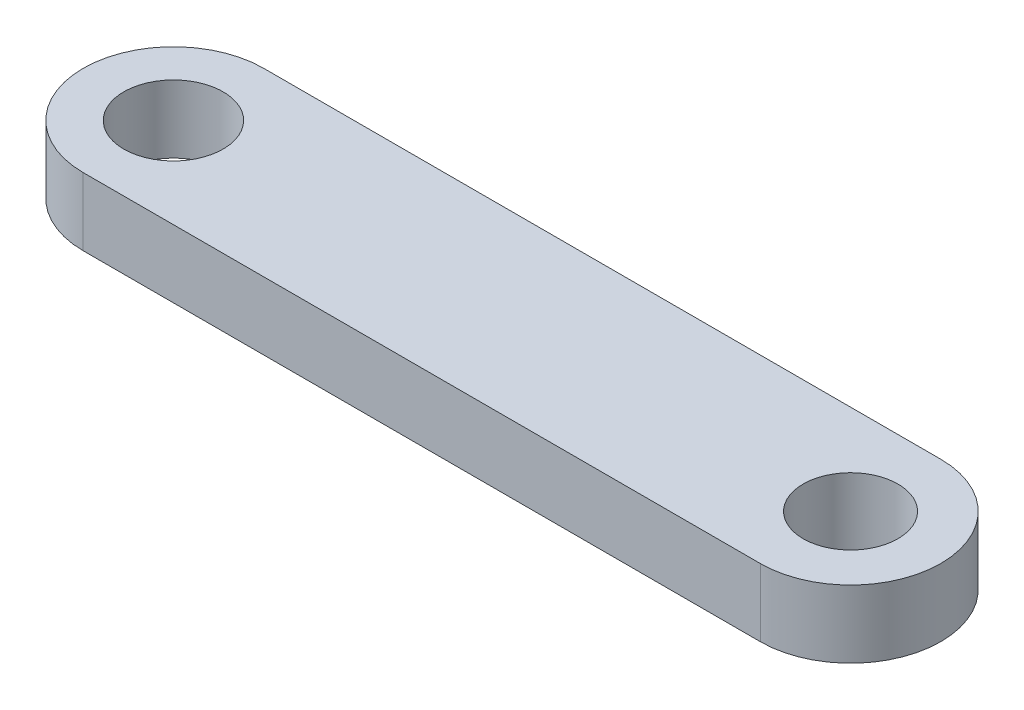
SolidWorks part; units mm, degrees
material "ABS"
ref_plane "Front Plane" through (0, 0, 0) normal (0, 0, 1) x (1, 0, 0)
ref_plane "Top Plane" through (0, 0, 0) normal (0, 1, 0) x (1, 0, 0)
ref_plane "Right Plane" through (0, 0, 0) normal (1, 0, 0) x (0, 0, -1)
sketch "Sketch1" plane through (0, 0, 0) normal (0, 1, 0) x (1, 0, 0)
  line L0 (-15, 0) -> (15, 0) construction
  line L1 (-15, 4) -> (15, 4)
  line L2 (-15, -4) -> (15, -4)
  arc A0 (-15, 4) -> (-15, -4) centre (-15, 0) ccw
  arc A1 (15, -4) -> (15, 4) centre (15, 0) ccw
  circle A2 centre (15, 0) radius 2.1
  circle A3 centre (-15, 0) radius 2.2
  point P2 (0, 0)
  dimension "D3" = 4.2
  dimension "D4" = 4.4
  dimension "D1" = 8
  dimension "D2" = 30
extrude "Boss-Extrude1" add sketch "Sketch1" along normal blind 3
